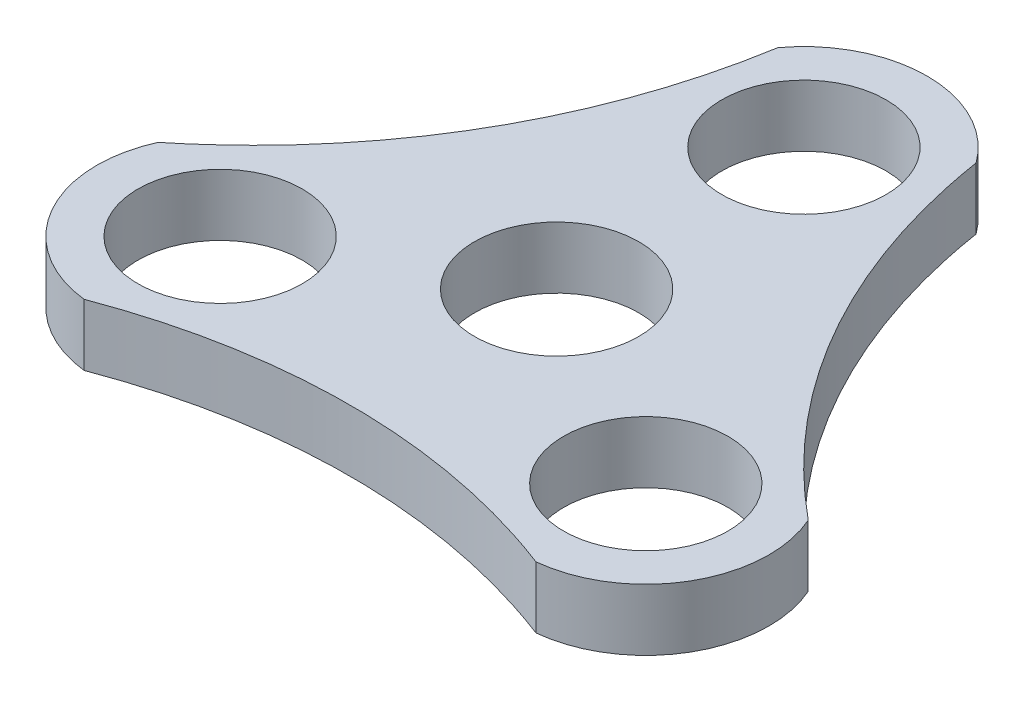
SolidWorks part; units mm, degrees
ref_plane "Front Plane" through (0, 0, 0) normal (0, 0, 1) x (1, 0, 0)
ref_plane "Top Plane" through (0, 0, 0) normal (0, 1, 0) x (1, 0, 0)
ref_plane "Right Plane" through (0, 0, 0) normal (1, 0, 0) x (0, 0, -1)
sketch "Sketch2" plane through (0, 0, 0) normal (0, 1, 0) x (1, 0, 0)
  line L0 (-7.6101, 24.6979) -> (-9.5921, 12.6494) construction
  line L1 (0.0597, 19.0499) -> (-16.5276, -9.4732) construction
  line L2 (-16.5276, -9.4732) -> (16.4678, -9.5767) construction
  line L3 (16.4678, -9.5767) -> (0.0597, 19.0499) construction
  line L4 (-13.7232, 7.9806) -> (-0.0498, -15.8749) construction
  line L5 (-0.0498, -15.8749) -> (13.773, 7.8943) construction
  line L6 (13.773, 7.8943) -> (-13.7232, 7.9806) construction
  line L7 (-15.7359, 2.0972) -> (-25.2242, -5.5881) construction
  line L8 (-9.5921, 12.6494) -> (-15.7359, 2.0972) construction
  line L9 (25.1878, -5.7441) -> (15.7437, 1.9957) construction
  line L10 (9.6762, 12.5918) -> (7.7635, 24.6515) construction
  line L11 (15.7437, 1.9957) -> (9.6762, 12.5918) construction
  line L12 (-17.5771, -18.9402) -> (-6.152, -14.632) construction
  line L13 (6.0583, -14.676) -> (17.4584, -19.05) construction
  line L14 (-6.152, -14.632) -> (6.0583, -14.676) construction
  circle A0 centre (0, 0) radius 6.35
  circle A1 centre (0, 0) radius 9.525 construction
  circle A2 centre (0, 0) radius 9.525 construction
  circle A3 centre (0.0597, 19.0499) radius 6.35
  circle A4 centre (16.4678, -9.5767) radius 6.35
  circle A5 centre (-16.5276, -9.4732) radius 6.35
  arc A6 (7.7635, 24.6515) -> (-7.6101, 24.6979) centre (0.0597, 19.0499) ccw
  arc A7 (17.4584, -19.05) -> (25.1878, -5.7441) centre (16.4678, -9.5767) ccw
  arc A8 (-25.2242, -5.5881) -> (-17.5771, -18.9402) centre (-16.5276, -9.4732) ccw
  circle A9 centre (0, 0) radius 15.875 construction
  circle A10 centre (0, 0) radius 7.9375 construction
  spline S0 degree 3 poles (-7.6101, 24.6979) (-9.5921, 12.6494) (-15.7359, 2.0972) (-25.2242, -5.5881) knots 0 0 0 0 1 1 1 1
  spline S1 degree 3 poles (25.1878, -5.7441) (15.7437, 1.9957) (9.6762, 12.5918) (7.7635, 24.6515) knots 0 0 0 0 1 1 1 1
  spline S2 degree 3 poles (-17.5771, -18.9402) (-6.152, -14.632) (6.0583, -14.676) (17.4584, -19.05) knots 0 0 0 0 1 1 1 1
  point P29 (0, 0.0079)
  point P34 (-0.0038, 0.0022)
  dimension "D1" = 12.7
  dimension "D2" = 19.05
  dimension "D3" = 19.05
  dimension "D4" = 31.75
  dimension "D5" = 2
  dimension "D6" = 2
extrude "Boss-Extrude1" add sketch "Sketch2" along normal blind 4.7625
